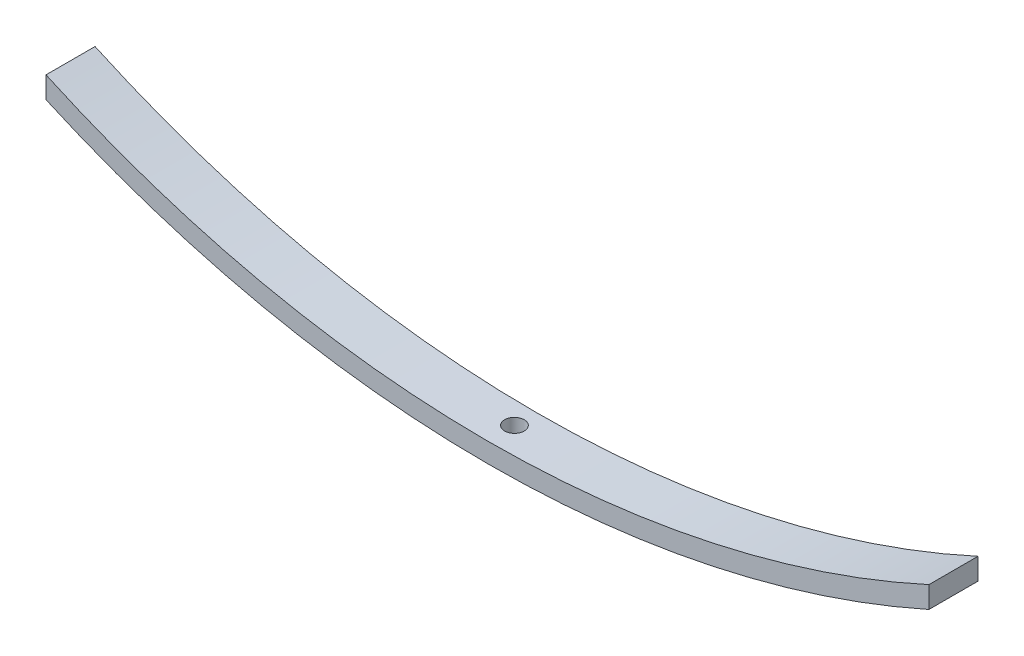
SolidWorks part; units mm, degrees
ref_plane "Front Plane" through (0, 0, 0) normal (0, 0, 1) x (1, 0, 0)
ref_plane "Top Plane" through (0, 0, 0) normal (0, 1, 0) x (1, 0, 0)
ref_plane "Right Plane" through (0, 0, 0) normal (1, 0, 0) x (0, 0, -1)
sketch "Sketch1" plane through (0, 0, 0) normal (0, 0, 1) x (1, 0, 0)
  line L0 (-450, -1003.743) -> (-450, -981.7841)
  line L1 (0, 0) -> (0, -3000.7365)
  line L2 (450, -1003.743) -> (450, -981.7841)
  arc A0 (-450, -1003.743) -> (450, -1003.743) centre (0, 0) ccw
  arc A1 (-450, -981.7841) -> (450, -981.7841) centre (0, 0) ccw
  point P7 (-450, -992.7635)
  dimension "D1" = 2200
  dimension "D2" = 2160
  dimension "D3" = 450
extrude "Boss-Extrude1" add sketch "Sketch1" along normal blind 50 contours A0 L2 A1 L0
sketch "Sketch3" plane through (0, 0, 0) normal (0, 1, 0) x (1, 0, 0)
  line L0 (0, 0) -> (0, -53.543) construction
  line L1 (450, 0) -> (-450, 0) construction
  circle A0 centre (0, -22.5) radius 10
  dimension "D1" = 20
  dimension "D2" = 22.5
extrude "Cut-Extrude1" cut sketch "Sketch3" against normal through all
